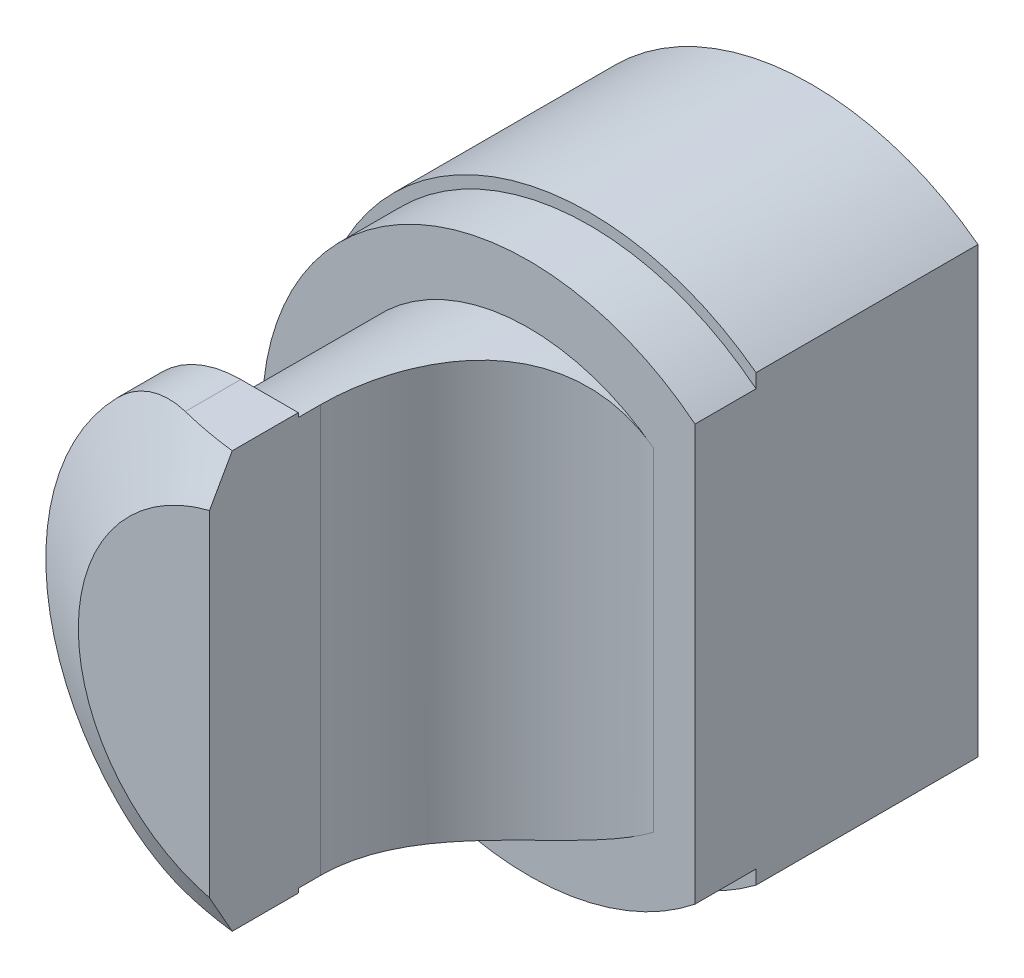
SolidWorks part; units mm, degrees
ref_plane "Front Plane" through (0, 0, 0) normal (0, 0, 1) x (1, 0, 0)
ref_plane "Top Plane" through (0, 0, 0) normal (0, 1, 0) x (1, 0, 0)
ref_plane "Right Plane" through (0, 0, 0) normal (1, 0, 0) x (0, 0, -1)
sketch "Sketch1" plane through (0, 0, 0) normal (0, 0, 1) x (1, 0, 0)
  circle A0 centre (0, 0) radius 2.4
  dimension "D1" = 4.8
extrude "Boss-Extrude1" add sketch "Sketch1" along normal blind 0.55
sketch "Sketch2" plane through (0, 0, 0.55) normal (0, 0, 1) x (1, 0, 0)
  circle A0 centre (0, 0) radius 1.875
  dimension "D1" = 3.75
extrude "Boss-Extrude2" add sketch "Sketch2" along normal blind 1.7
sketch "Sketch3" plane through (0, 0, 0) normal (0, 0, -1) x (-1, 0, 0)
  circle A0 centre (0, 0) radius 2.5
  dimension "D1" = 5
extrude "Boss-Extrude3" add sketch "Sketch3" along normal blind 2
sketch "Sketch4" plane through (0, 0, 2.25) normal (0, 0, 1) x (1, 0, 0)
  circle A0 centre (0, 0) radius 2.25
  dimension "D1" = 4.5
extrude "Boss-Extrude4" add sketch "Sketch4" along normal blind 0.8
sketch "Sketch5" plane through (0, 0, 3.05) normal (0, 0, 1) x (1, 0, 0)
  line L1 (-0.375, -3.0369) -> (0.375, -3.0369)
  line L2 (-0.375, -3.0369) -> (-0.375, 3.0369)
  line L3 (-0.375, 3.0369) -> (0.375, 3.0369)
  line L4 (0.375, -3.0369) -> (0.375, 3.0369)
  line L5 (-0.375, -3.0369) -> (0.375, 3.0369) construction
  line L6 (-0.375, 3.0369) -> (0.375, -3.0369) construction
  point P0 (0, 0)
  dimension "D1" = 0.75
extrude "Cut-Extrude1" cut sketch "Sketch5" against normal up to surface (2.5 mm away) up to face at (1.875, 0, 0.55)
chamfer "Chamfer1" distance 0.4 angle 60 2 edges at (-2.25, 0, 3.05) (2.25, 0, 3.05)
sketch "Sketch6" plane through (0, 0, 3.05) normal (0, 0, 1) x (1, 0, 0)
  line L1 (-3.2793, -1.875) -> (3.2793, -1.875)
  line L2 (-3.2793, -1.875) -> (-3.2793, 1.875)
  line L3 (-3.2793, 1.875) -> (3.2793, 1.875)
  line L4 (3.2793, -1.875) -> (3.2793, 1.875)
  line L5 (-3.2793, -1.875) -> (3.2793, 1.875) construction
  line L6 (-3.2793, 1.875) -> (3.2793, -1.875) construction
  line L7 (-3.4518, 2.624) -> (3.5474, 2.624)
  line L8 (-3.4518, 2.624) -> (-3.4518, -2.711)
  line L9 (-3.4518, -2.711) -> (3.5474, -2.711)
  line L10 (3.5474, 2.624) -> (3.5474, -2.711)
  point P0 (0, 0)
  dimension "D1" = 3.75
extrude "Cut-Extrude3" cut sketch "Sketch6" against normal blind 2
fillet "Fillet2" radius 1 4 edges at (-1.2437, 1.875, 2.45) (1.2437, 1.875, 2.45) (-1.2437, -1.875, 2.45) (1.2437, -1.875, 2.45)
sketch "Sketch7" plane through (0, 0, -2) normal (0, 0, -1) x (-1, 0, 0)
  circle A0 centre (0, 0) radius 1
  dimension "D1" = 2
extrude "Cut-Extrude4" cut sketch "Sketch7" against normal blind 2
sketch "Sketch8" plane through (0, 0, 0) normal (0, 1, 0) x (1, 0, 0)
  line L2 (-0.8927, -2.25) -> (-1.6068, -2.25) construction
  line L5 (-0.375, -2.25) -> (-0.375, -0.55) construction
  line L7 (-0.625, -1.25) -> (0, -1.25)
  line L8 (0, -1.25) -> (0, -2.25)
  line L9 (0, -2.25) -> (-0.625, -2.25)
  circle A0 centre (-0.625, -1.75) radius 0.5
  dimension "D1" = 1
  dimension "D2" = 0.5
  dimension "D3" = 0.25
sketch "Sketch9" plane through (0, 0, 0) normal (0, 1, 0) x (1, 0, 0)
  line L0 (-2.4, -0.55) -> (2.4, -0.55) construction
  line L1 (0, -0.55) -> (3.3094, -0.55)
  line L2 (0, -0.55) -> (0, -3.4709)
  line L3 (0, -3.4709) -> (3.3094, -3.4709)
  line L4 (3.3094, -0.55) -> (3.3094, -3.4709)
extrude "Cut-Extrude5" cut sketch "Sketch9" along normal blind 3 and the other way blind 10
fillet "Fillet3" radius 1.5 1 edges at (-0.375, 0, 0.55)
sketch "Sketch10" plane through (0, 0, 0.55) normal (0, 0, 1) x (1, 0, 0)
  line L1 (1.5, 3.3362) -> (4.4501, 3.3362)
  line L2 (1.5, 3.3362) -> (1.5, -3.1616)
  line L3 (1.5, -3.1616) -> (4.4501, -3.1616)
  line L4 (4.4501, 3.3362) -> (4.4501, -3.1616)
  dimension "D1" = 1.5
extrude "Cut-Extrude6" cut sketch "Sketch10" against normal blind 10
